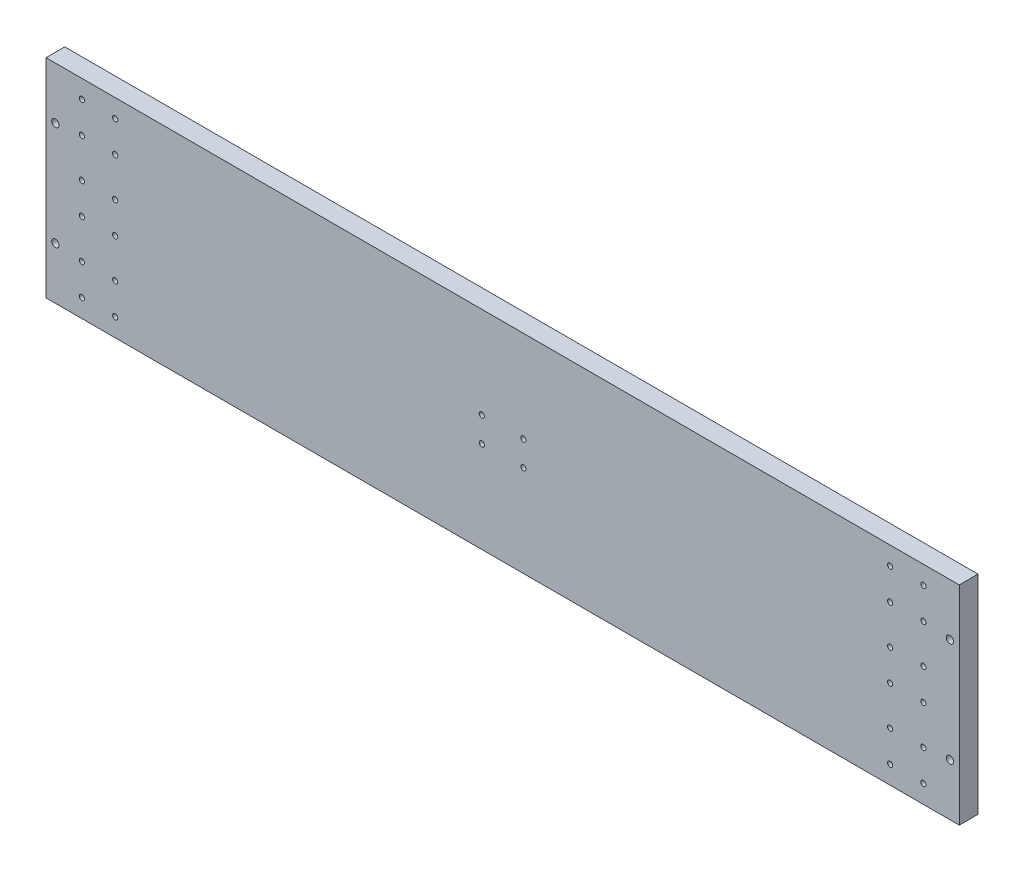
SolidWorks part; units mm, degrees
ref_plane "Front Plane" through (0, 0, 0) normal (0, 0, 1) x (1, 0, 0)
ref_plane "Top Plane" through (0, 0, 0) normal (0, 1, 0) x (1, 0, 0)
ref_plane "Right Plane" through (0, 0, 0) normal (1, 0, 0) x (0, 0, -1)
sketch "Sketch1" plane through (0, 0, 0) normal (0, 0, 1) x (1, 0, 0)
  line L1 (-439, 100) -> (439, 100)
  line L2 (-439, 100) -> (-439, -100)
  line L3 (-439, -100) -> (439, -100)
  line L4 (439, 100) -> (439, -100)
  line L5 (-439, 100) -> (439, -100) construction
  line L6 (-439, -100) -> (439, 100) construction
  point P0 (0, 0)
  dimension "D1" = 878
  dimension "D2" = 200
extrude "Boss-Extrude1" add sketch "Sketch1" along normal blind 18
hole_wizard "Otwór Ø7.0 (7)1" positions "Szkic4" profile "Szkic3" hole size "Ø7.0" standard "ISO" end condition through all
sketch "Szkic4" plane through (0, 0, 0) normal (0, 0, -1) x (-1, 0, 0)
  point P0 (-430, 50)
  point P3 (-430, -50)
sketch "Szkic3" plane through (430, 50, 0) normal (1, 0, 0) x (0, 1, 0)
  line L0 (0, 0) -> (0, 18)
  line L1 (0, 18) -> (3.5, 18)
  line L2 (3.5, 18) -> (3.5, 0)
  line L5 (3.5, 0) -> (0, 0)
  line L11 (0, -6.35) -> (0, 107.95) construction
  dimension "Średnica otworu na wylot" = 7
  dimension "Głębokość otworu na wylot" = 18
ref_plane "Płaszczyzna1" through (0, 0, 0) normal (-1, 0, 0) x (0, 0, 1)
mirror "Lustro1" about plane through (0, 0, 0) normal (-1, 0, 0) of "Otwór Ø7.0 (7)1"
hole_wizard "Otwór Ø5.0 (5)1" positions "Szkic6" profile "Szkic5" hole size "Ø5.0" standard "ISO" end condition through all
sketch "Szkic6" plane through (0, 0, 18) normal (0, 0, 1) x (1, 0, 0)
  point P0 (372.5, 82.5)
  point P2 (372.5, 52.5)
  point P4 (404.5, 82.5)
  point P6 (404.5, 52.5)
  point P8 (404.5, 15)
  point P10 (404.5, -15)
  point P12 (372.5, 15)
  point P14 (372.5, -15)
  point P16 (372.5, -52.5)
  point P18 (372.5, -82.5)
  point P20 (404.5, -52.5)
  point P22 (404.5, -82.5)
  point P32 (-372.5, 82.5)
  point P34 (-372.5, 52.5)
  point P36 (-404.5, 52.5)
  point P38 (-404.5, 82.5)
  point P40 (-372.5, 15)
  point P42 (-372.5, -15)
  point P44 (-404.5, -15)
  point P46 (-404.5, 15)
  point P48 (-372.5, -82.5)
  point P50 (-372.5, -52.5)
  point P52 (-404.5, -52.5)
  point P54 (-404.5, -82.5)
sketch "Szkic5" plane through (372.5, 82.5, 18) normal (1, 0, 0) x (0, -1, 0)
  line L0 (0, 0) -> (0, 18)
  line L1 (0, 18) -> (2.5, 18)
  line L2 (2.5, 18) -> (2.5, 0)
  line L5 (2.5, 0) -> (0, 0)
  line L11 (0, -6.35) -> (0, 107.95) construction
  dimension "Średnica otworu na wylot" = 5
  dimension "Głębokość otworu na wylot" = 18
hole_wizard "Otwór Ø10.0 (10)1" positions "Szkic8" profile "Szkic7" hole size "Ø10.0" standard "ISO"
sketch "Szkic8" plane through (0, 0, 0) normal (0, 0, -1) x (-1, 0, 0)
  point P0 (372.5, 82.5)
  point P3 (372.5, 52.5)
  point P6 (372.5, 15)
  point P9 (372.5, -15)
  point P12 (372.5, -52.5)
  point P15 (372.5, -82.5)
  point P18 (404.5, -82.5)
  point P21 (404.5, -52.5)
  point P24 (404.5, -15)
  point P27 (404.5, 15)
  point P30 (404.5, 52.5)
  point P33 (404.5, 82.5)
  point P48 (-372.5, -82.5)
  point P51 (-404.5, -82.5)
  point P54 (-404.5, -52.5)
  point P57 (-372.5, -52.5)
  point P60 (-372.5, -15)
  point P63 (-404.5, -15)
  point P66 (-404.5, 15)
  point P69 (-372.5, 15)
  point P72 (-372.5, 52.5)
  point P75 (-404.5, 52.5)
  point P78 (-404.5, 82.5)
  point P81 (-372.5, 82.5)
sketch "Szkic7" plane through (-372.5, 82.5, 0) normal (1, 0, 0) x (0, 1, 0)
  line L0 (0, 0) -> (0, 7)
  line L1 (0, 7) -> (5, 7)
  line L2 (5, 7) -> (5, 0)
  line L5 (5, 0) -> (0, 0)
  line L10 (0, 7) -> (-5, 7) construction
  line L11 (0, -6.35) -> (0, 107.95) construction
  dimension "Średnica otworu" = 10
  dimension "Głębokość otworu" = 7
  dimension "Kąt wiertła" = 180
hole_wizard "Otwór Ø5.0 (5)2" positions "Szkic10" profile "Szkic9" hole size "Ø5.0" standard "ISO" end condition through all
sketch "Szkic10" plane through (0, 0, 18) normal (0, 0, 1) x (1, 0, 0)
  line L1 (-439, 100) -> (-439, -100) construction
  line L3 (-439, -100) -> (439, -100) construction
  point P0 (-20, 12)
  point P2 (20, 12)
  point P4 (20, -12)
  point P6 (-20, -12)
  dimension "D1" = 40
  dimension "D2" = 40
  dimension "D3" = 24
  dimension "D4" = 24
  dimension "D5" = 419
  dimension "D6" = 88
  dimension "D7" = 88
sketch "Szkic9" plane through (-20, 12, 18) normal (1, 0, 0) x (0, -1, 0)
  line L0 (0, 0) -> (0, 18)
  line L1 (0, 18) -> (2.5, 18)
  line L2 (2.5, 18) -> (2.5, 0)
  line L5 (2.5, 0) -> (0, 0)
  line L11 (0, -6.35) -> (0, 107.95) construction
  dimension "Średnica otworu na wylot" = 5
  dimension "Głębokość otworu na wylot" = 18
hole_wizard "Otwór Ø10.0 (10)2" positions "Szkic12" profile "Szkic11" hole size "Ø10.0" standard "ISO"
sketch "Szkic12" plane through (0, 0, 0) normal (0, 0, -1) x (-1, 0, 0)
  point P0 (20, 12)
  point P3 (20, -12)
  point P6 (-20, -12)
  point P9 (-20, 12)
sketch "Szkic11" plane through (-20, 12, 0) normal (1, 0, 0) x (0, 1, 0)
  line L0 (0, 0) -> (0, 7)
  line L1 (0, 7) -> (5, 7)
  line L2 (5, 7) -> (5, 0)
  line L5 (5, 0) -> (0, 0)
  line L10 (0, 7) -> (-5, 7) construction
  line L11 (0, -6.35) -> (0, 107.95) construction
  dimension "Średnica otworu" = 10
  dimension "Głębokość otworu" = 7
  dimension "Kąt wiertła" = 180
hole_wizard "Otwór Ø8.0 (8)1" positions "Szkic14" profile "Szkic13" hole size "Ø8.0" standard "ISO"
sketch "Szkic14" plane through (0, 0, 0) normal (0, 0, -1) x (-1, 0, 0)
  point P0 (430, 0)
  point P2 (-430, 0)
sketch "Szkic13" plane through (-430, 0, 0) normal (1, 0, 0) x (0, 1, 0)
  line L0 (0, 0) -> (0, 17.4034)
  line L1 (0, 17.4034) -> (4, 15)
  line L2 (4, 15) -> (4, 0)
  line L5 (4, 0) -> (0, 0)
  line L10 (0, 17.4034) -> (-4, 15) construction
  line L11 (0, -6.35) -> (0, 107.95) construction
  dimension "Średnica otworu" = 8
  dimension "Głębokość otworu" = 15
  dimension "Kąt wiertła" = 118
